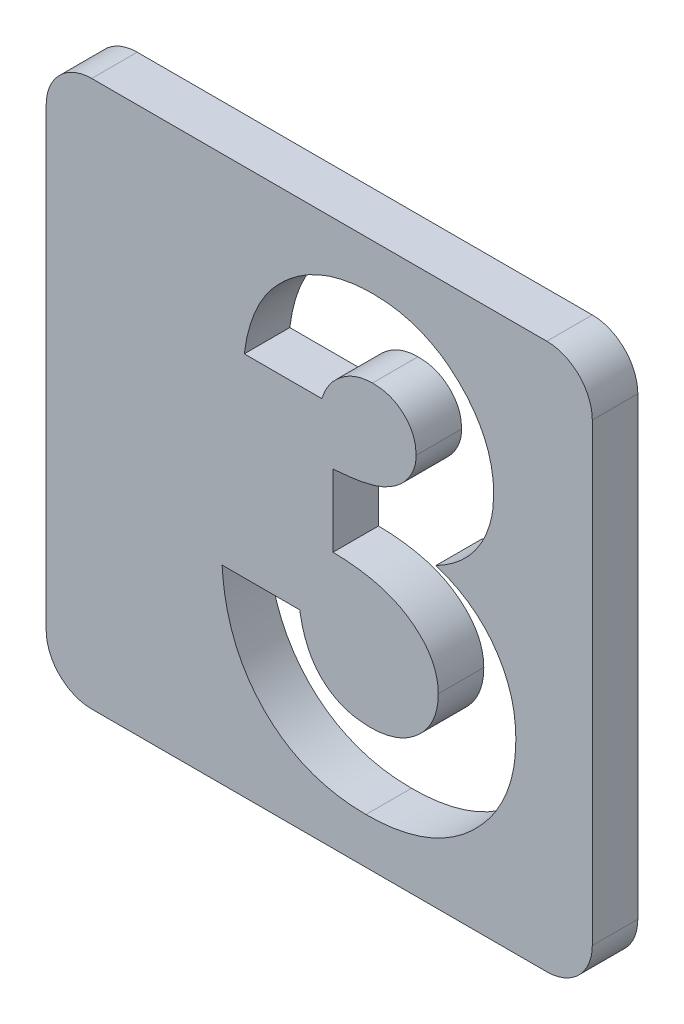
SolidWorks part; units mm, degrees
ref_plane "Front Plane" through (0, 0, 0) normal (0, 0, 1) x (1, 0, 0)
ref_plane "Top Plane" through (0, 0, 0) normal (0, 1, 0) x (1, 0, 0)
ref_plane "Right Plane" through (0, 0, 0) normal (1, 0, 0) x (0, 0, -1)
sketch "Sketch1" plane through (0, 0, 0) normal (0, 0, 1) x (1, 0, 0)
  line L1 (-50, 60) -> (50, 60)
  line L2 (-60, 50) -> (-60, -50)
  line L3 (-50, -60) -> (50, -60)
  line L4 (60, 50) -> (60, -50)
  line L5 (-60, 60) -> (60, -60) construction
  line L6 (-60, -60) -> (60, 60) construction
  arc A0 (-60, -50) -> (-50, -60) centre (-50, -50) ccw
  arc A1 (50, -60) -> (60, -50) centre (50, -50) ccw
  arc A2 (50, 60) -> (60, 50) centre (50, 50) cw
  arc A3 (-50, 60) -> (-60, 50) centre (-50, 50) ccw
  point P0 (0, 0)
  dimension "D3" = 10
  dimension "D1" = 120
  dimension "D2" = 120
extrude "Boss-Extrude1" add sketch "Sketch1" along normal blind 10 contours A3 L2 A0 L3 A1 L4 A2 L1
sketch "Sketch2" plane through (0, 0, 10) normal (0, 0, 1) x (1, 0, 0)
  line L0 (0, 0) -> (0, 40) construction
  line L1 (-50, 50) -> (50, 50) construction
  line L2 (-50, 50) -> (-50, -50) construction
  line L3 (-50, -50) -> (50, -50) construction
  line L4 (50, 50) -> (50, -50) construction
  line L5 (-50, 50) -> (50, -50) construction
  line L6 (-50, -50) -> (50, 50) construction
  line L7 (0, 40) -> (-40, 40) construction
  line L8 (-40, 40) -> (-40, 0) construction
  line L9 (-40, 0) -> (0, 0) construction
  line L11 (0, 20) -> (-20, 20) construction
  line L12 (-20, 40) -> (-20, 20) construction
  circle A0 centre (0, 40) radius 4 construction
  circle A1 centre (0, 20) radius 4 construction
  circle A2 centre (0, 0) radius 4 construction
  circle A3 centre (-20, 20) radius 4 construction
  circle A4 centre (-20, 40) radius 4 construction
  circle A5 centre (-40, 40) radius 4 construction
  circle A6 centre (0, 0) radius 4 construction
  circle A7 centre (20, 0) radius 4 construction
  circle A8 centre (40, 0) radius 4 construction
  circle A9 centre (40, 20) radius 4 construction
  circle A10 centre (40, 40) radius 4 construction
  circle A11 centre (20, 20) radius 4 construction
  circle A12 centre (0, 0) radius 4 construction
  circle A13 centre (0, -20) radius 4 construction
  circle A14 centre (0, -40) radius 4 construction
  circle A15 centre (20, -40) radius 4 construction
  circle A16 centre (40, -40) radius 4 construction
  circle A17 centre (20, -20) radius 4 construction
  circle A18 centre (0, 0) radius 4 construction
  circle A19 centre (-20, 0) radius 4 construction
  circle A20 centre (-40, 0) radius 4 construction
  circle A21 centre (-40, -20) radius 4 construction
  circle A22 centre (-40, -40) radius 4 construction
  circle A23 centre (-20, -20) radius 4 construction
  text T0 "3" font "Century Gothic" height 95
  point P0 (0, 0)
  point P55 (0, 0)
  dimension "D4" = 8
  dimension "D1" = 100
  dimension "D2" = 100
  dimension "D3" = 40
  dimension "D5" = 4
extrude "Cut-Extrude1" cut sketch "Sketch2" against normal blind 10
